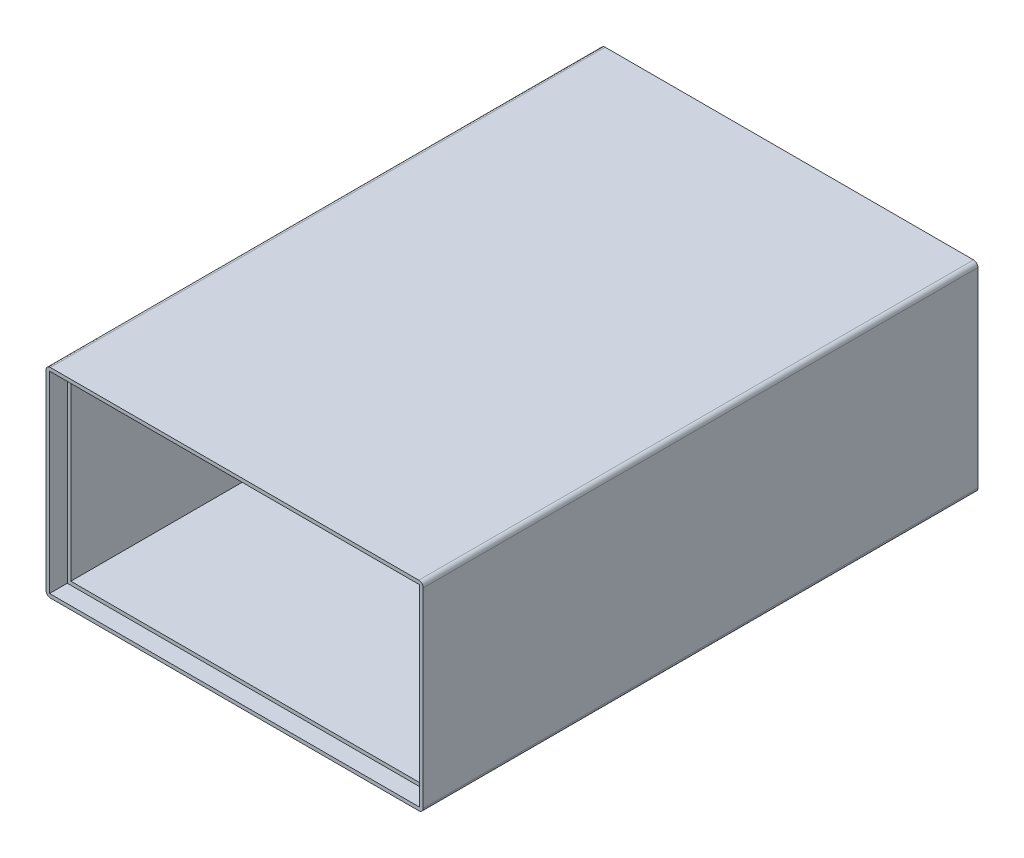
SolidWorks part; units mm, degrees
material "ABS"
ref_plane "Спереди" through (0, 0, 0) normal (0, 0, 1) x (1, 0, 0)
ref_plane "Сверху" through (0, 0, 0) normal (0, 1, 0) x (1, 0, 0)
ref_plane "Справа" through (0, 0, 0) normal (1, 0, 0) x (0, 0, -1)
sketch "Эскиз1" plane through (0, 0, 0) normal (0, 0, 1) x (1, 0, 0)
  line L1 (0, 0) -> (85, 0)
  line L2 (0, 0) -> (0, 45)
  line L3 (0, 45) -> (85, 45)
  line L4 (85, 0) -> (85, 45)
  dimension "D1" = 85
  dimension "D2" = 45
extrude "Бобышка-Вытянуть1" add sketch "Эскиз1" along normal blind 125
sketch "Эскиз2" plane through (0, 0, 125) normal (0, 0, 1) x (1, 0, 0)
  line L0 (42.5, 45) -> (42.5, 0) construction
  line L1 (85, 45) -> (0, 45) construction
  line L2 (0, 0) -> (85, 0) construction
  line L3 (85, 0) -> (85, 45) construction
  line L4 (1.6, 43.4) -> (83.4, 43.4)
  line L5 (1.6, 43.4) -> (1.6, 1.6)
  line L6 (1.6, 1.6) -> (83.4, 1.6)
  line L7 (83.4, 43.4) -> (83.4, 1.6)
  line L8 (1.6, 43.4) -> (83.4, 1.6) construction
  line L9 (1.6, 1.6) -> (83.4, 43.4) construction
  point P6 (42.5, 22.5)
  dimension "D1" = 1.6
  dimension "D2" = 1.6
extrude "Вырез-Вытянуть1" cut sketch "Эскиз2" against normal blind 123.4
sketch "Эскиз3" plane through (0, 0, 125) normal (0, 0, 1) x (1, 0, 0)
  line L0 (42.5, 45) -> (42.5, 0) construction
  line L1 (85, 45) -> (0, 45) construction
  line L2 (0, 0) -> (85, 0) construction
  line L3 (0, 45) -> (0, 0) construction
  line L4 (0.8, 44.2) -> (84.2, 44.2)
  line L5 (0.8, 44.2) -> (0.8, 0.8)
  line L6 (0.8, 0.8) -> (84.2, 0.8)
  line L7 (84.2, 44.2) -> (84.2, 0.8)
  line L8 (0.8, 44.2) -> (84.2, 0.8) construction
  line L9 (0.8, 0.8) -> (84.2, 44.2) construction
  circle A0 centre (42.5, 22.5) radius 52.5648 construction
  point P6 (42.5, 22.5)
  dimension "D1" = 0.8
  dimension "D2" = 0.8
extrude "Вырез-Вытянуть2" cut sketch "Эскиз3" against normal blind 4
fillet "Скругление2" radius 1 4 edges at (0, 45, 62.5) (85, 45, 62.5) (85, 0, 62.5) (0, 0, 62.5)
